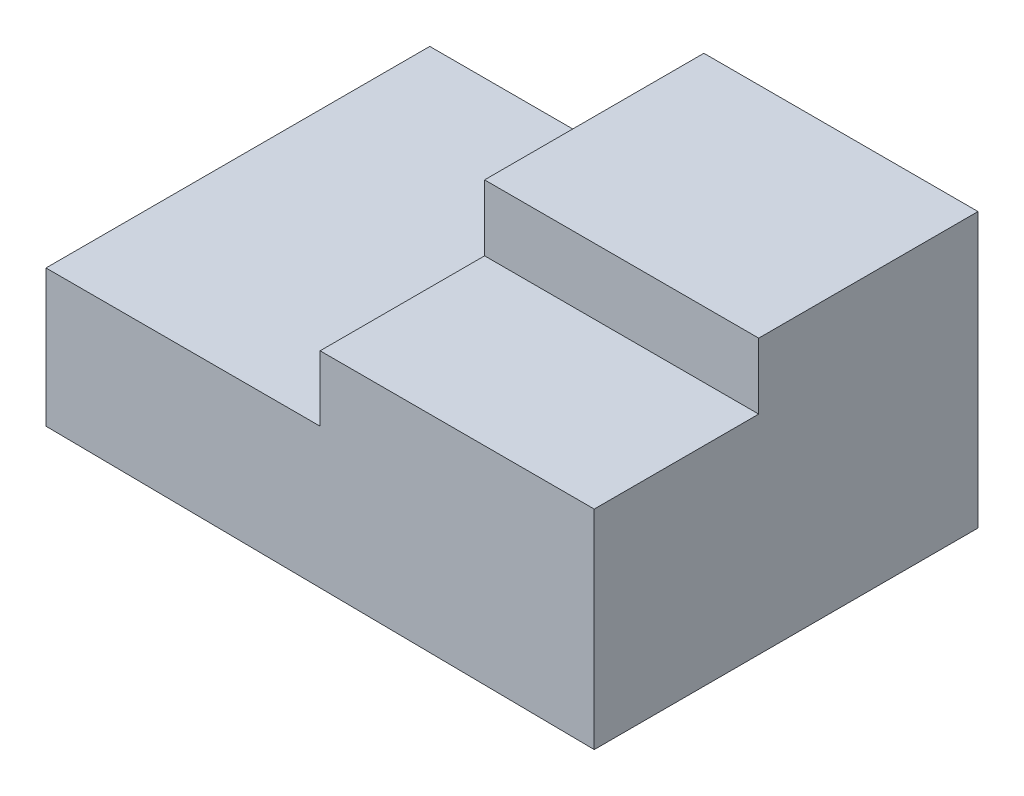
SolidWorks part; units mm, degrees
ref_plane "Front Plane" through (0, 0, 0) normal (0, 0, 1) x (1, 0, 0)
ref_plane "Top Plane" through (0, 0, 0) normal (0, 1, 0) x (1, 0, 0)
ref_plane "Right Plane" through (0, 0, 0) normal (1, 0, 0) x (0, 0, -1)
sketch "Sketch1" plane through (0, 0, 0) normal (0, 0, 1) x (1, 0, 0)
  line L0 (0, 0) -> (100, -1.085)
  line L1 (100, -1.085) -> (100, 36.915)
  line L2 (100, 36.915) -> (50, 36.915)
  line L3 (50, 36.915) -> (50, 25)
  line L4 (50, 25) -> (0, 25)
  line L5 (0, 25) -> (0, 0)
  dimension "D1" = 100
  dimension "D2" = 38
  dimension "D3" = 25
extrude "Boss-Extrude1" add sketch "Sketch1" along normal blind 70 contours L5 L0 L1 L2 L3 L4
sketch "Sketch2" plane through (0, 36.915, 0) normal (0, 1, 0) x (1, 0, 0)
  line L0 (100, -70) -> (100, 0) construction
  line L1 (100, 0) -> (100, -40)
  line L2 (100, -40) -> (50, -40)
  line L3 (50, -70) -> (50, 0) construction
  line L4 (50, -40) -> (50, 0)
  line L5 (50, 0) -> (100, 0)
  dimension "D1" = 40
extrude "Boss-Extrude2" add sketch "Sketch2" along normal blind 12 contours L5 L1 L2 L4
